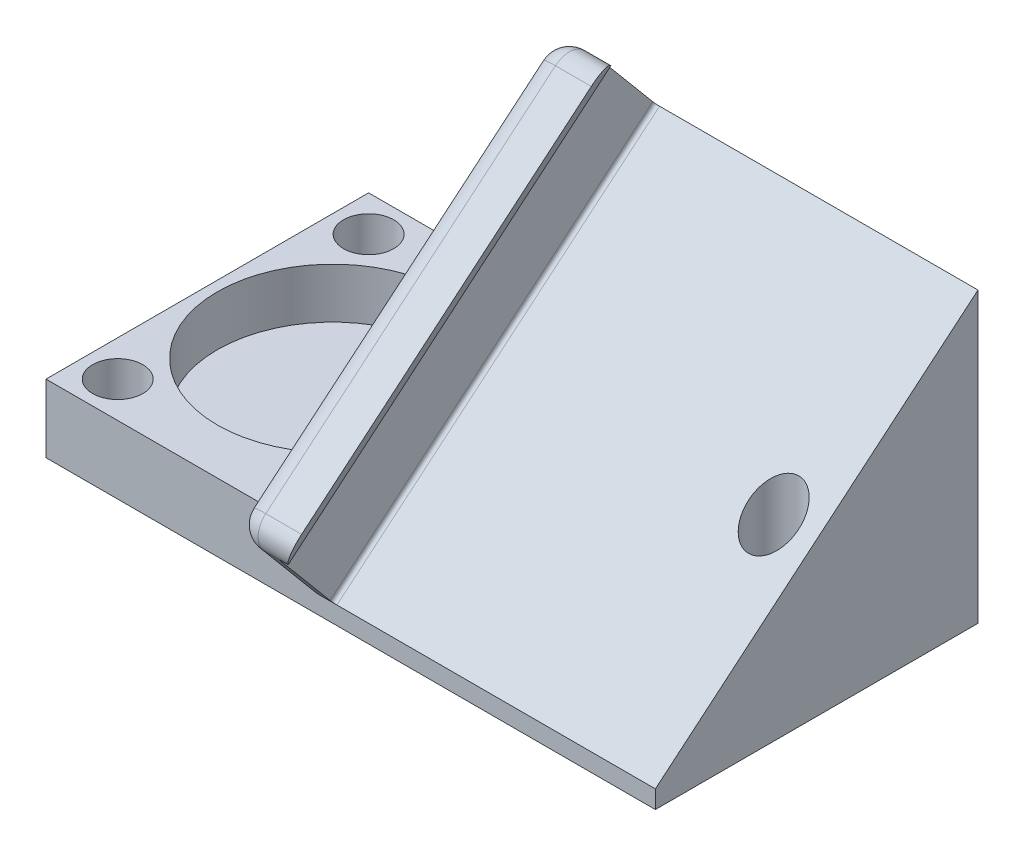
SolidWorks part; units mm, degrees
ref_plane "Front Plane" through (0, 0, 0) normal (0, 0, 1) x (1, 0, 0)
ref_plane "Top Plane" through (0, 0, 0) normal (0, 1, 0) x (1, 0, 0)
ref_plane "Right Plane" through (0, 0, 0) normal (1, 0, 0) x (0, 0, -1)
sketch "Sketch1" plane through (0, 0, 0) normal (0, 1, 0) x (1, 0, 0)
  line L1 (0, 0) -> (-85, 0)
  line L2 (0, 0) -> (0, 45)
  line L3 (0, 45) -> (-85, 45)
  line L4 (-85, 0) -> (-85, 45)
  dimension "D1" = 85
  dimension "D2" = 45
extrude "Boss-Extrude1" add sketch "Sketch1" along normal blind 2.5
sketch "Sketch2" plane through (0, 0, 0) normal (1, 0, 0) x (0, 0, -1)
  line L0 (0, 2.5) -> (45, 40.2595)
  line L1 (45, 40.2595) -> (45, 2.5)
  line L2 (45, 2.5) -> (0, 2.5)
  dimension "D3" = 40
extrude "Boss-Extrude2" add sketch "Sketch2" against normal blind 50
ref_plane "Plane1" through (-50, 40.2595, -45) normal (0, -0.6428, 0.766) x (1, 0, 0)
sketch "Sketch3" plane through (-50, 40.2595, -45) normal (0, -0.6428, 0.766) x (1, 0, 0)
  line L0 (0, 0) -> (0, 15)
  line L1 (0, 15) -> (8, 15)
  line L2 (8, 15) -> (6.5, 12)
  line L4 (5, 0) -> (0, 0)
  line L6 (6.5, 12) -> (5, 12)
  line L7 (5, 12) -> (5, 0)
  dimension "D1" = 5
  dimension "D2" = 8
  dimension "D3" = 3
  dimension "D4" = 1.5
extrude "Boss-Extrude3" add sketch "Sketch3" along normal up to vertex (58.7433 mm away) up to point (-50, 2.5, 0)
sketch "Sketch4" plane through (0, 2.5, 0) normal (0, 1, 0) x (1, 0, 0)
  line L0 (-50, 45) -> (-85, 0) construction
  line L1 (-50, 45) -> (-85, 45)
  line L2 (-50, 45) -> (-50, 0)
  line L3 (-50, 0) -> (-85, 0)
  line L4 (-85, 45) -> (-85, 0)
  circle A0 centre (-67.5, 22.5) radius 16.1
  line M5 (-85, 0) -> (-50, 0)
  line M6 (-50, 0) -> (-50, 45)
  line M7 (-50, 45) -> (-85, 45)
  line M8 (-85, 45) -> (-85, 0)
  dimension "D1" = 32.2
extrude "Boss-Extrude4" add sketch "Sketch4" along normal blind 7 contours L0 A0 M6 M5 | L0 A0 M7 M8 | L2 L1 L4 L3
sketch "Sketch5" plane through (0, 9.5, 0) normal (0, 1, 0) x (1, 0, 0)
  line L0 (-85, 0) -> (-50, 0) construction
  line L1 (-85, 45) -> (-85, 0) construction
  line L2 (-50, 45) -> (-85, 45) construction
  point P0 (-80, 40)
  point P1 (-80, 5)
  dimension "D1" = 5
  dimension "D2" = 5
  dimension "D3" = 5
  dimension "D4" = 5
hole_wizard "Hole1" positions "3DSketch1" profile "Sketch7" legacy
sketch3d "3DSketch1"
  point P0 (-80, 9.5, -40)
  point P3 (-80, 9.5, -5)
sketch "Sketch7" plane through (-80, 9.5, -40) normal (1, 0, 0) x (0, 0, 1)
  line L0 (0, 0) -> (0, 20)
  line L1 (0, 20) -> (2.1, 20)
  line L2 (2.1, 20) -> (2.1, 5)
  line L3 (2.1, 5) -> (3.5, 5)
  line L4 (3.5, 5) -> (3.5, 0)
  line L5 (3.5, 0) -> (0, 0)
  line L6 (0, 110) -> (0, -10) construction
  dimension "Diameter" = 4.2
  dimension "Depth" = 20
  dimension "C-Bore Diameter" = 7
  dimension "C-Bore Depth" = 5
ref_plane "Plane2" through (0, 0, -22.5) normal (0, 0, 1) x (1, 0, 0)
sketch "Sketch8" plane through (0, 0, -22.5) normal (0, 0, 1) x (1, 0, 0)
  line L0 (0, 21.3797) -> (-12, 21.3797) construction
  line L1 (0, 40.2595) -> (0, 2.5) construction
  line L2 (-6, 21.3797) -> (-6, 4.102) construction
  line L3 (-2.5, 21.3797) -> (-2.5, 6)
  line L4 (-2.5, 6) -> (-3.9, 6)
  line L5 (-3.9, 6) -> (-3.9, -6.5196)
  line L6 (-3.9, -6.5196) -> (-6, -6.5196)
  line L7 (-6, -6.5196) -> (-6, 21.3797)
  line L9 (-6, 21.3797) -> (-6, 29.2636)
  line L10 (-6, 29.2636) -> (-2.5, 29.2636)
  line L11 (-2.5, 29.2636) -> (-2.5, 21.3797)
  line L12 (-85, 0) -> (0, 0) construction
  dimension "D1" = 3.5
  dimension "D2" = 2.1
  dimension "D3" = 6
  dimension "D4" = 6
revolve "Cut-Revolve1" cut sketch "Sketch8" angle 360 about L7
fillet "Fillet4" radius 3 1 edges at (-50, 32.8704, -12.8582)
fillet "Fillet5" radius 3 4 edges at (-44.5, 51.7502, -35.3582) (-49.1213, 51.077, -35.923) (-50, 44.8558, -41.1433) (-50, 24.8797, -45)
fillet "Fillet6" radius 3 3 edges at (-44.5, 13.9907, 9.6418) (-49.1213, 13.3176, 9.077) (-50, 7.0963, 3.8567)
fillet "Fillet7" radius 0.58 2 edges at (-45, 21.3797, -22.5) (-45, 30.5723, -14.7865)
